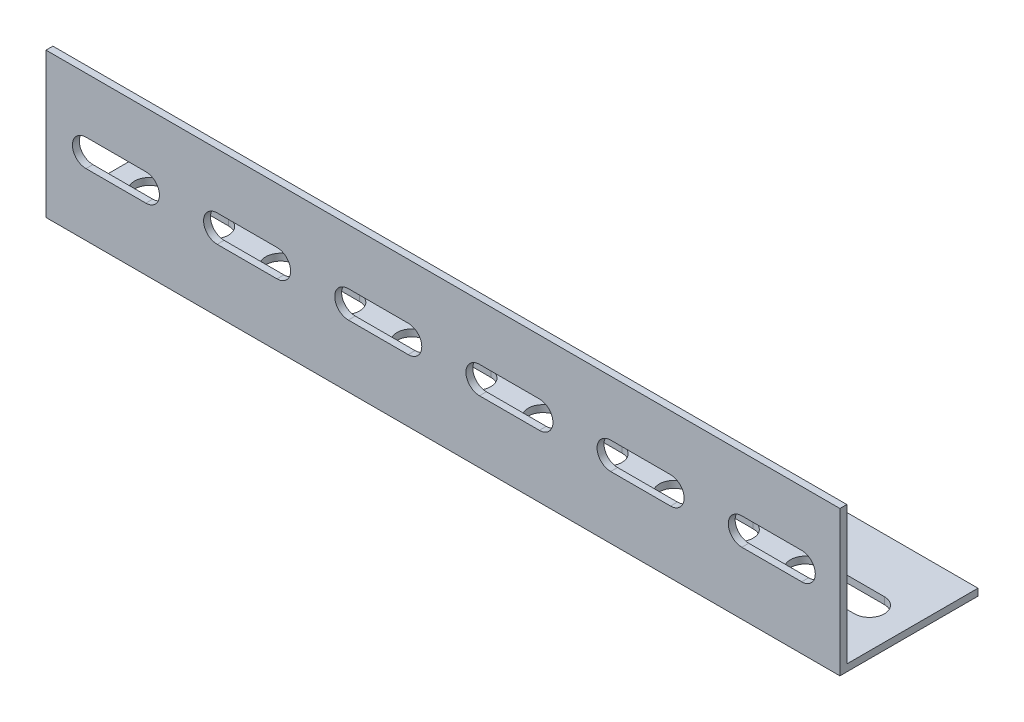
SolidWorks part; units mm, degrees
ref_plane "Front Plane" through (0, 0, 0) normal (0, 0, 1) x (1, 0, 0)
ref_plane "Top Plane" through (0, 0, 0) normal (0, 1, 0) x (1, 0, 0)
ref_plane "Right Plane" through (0, 0, 0) normal (1, 0, 0) x (0, 0, -1)
sketch "Sketch1" plane through (0, 0, 0) normal (0, 1, 0) x (1, 0, 0)
  line L1 (-75, 20) -> (75, 20)
  line L2 (-75, 20) -> (-75, -20)
  line L3 (-75, -20) -> (75, -20)
  line L4 (75, 20) -> (75, -20)
  line L5 (-75, 20) -> (75, -20) construction
  line L6 (-75, -20) -> (75, 20) construction
  point P0 (0, 0)
  dimension "D1" = 150
  dimension "D2" = 40
extrude "Boss-Extrude1" add sketch "Sketch1" along normal blind 2
sketch "Sketch2" plane through (0, 2, 0) normal (0, 1, 0) x (1, 0, 0)
  line L0 (75, -20) -> (75, 20) construction
  line L1 (-75, -20) -> (75, -20)
  line L2 (-75, -20) -> (-75, -18)
  line L3 (-75, -18) -> (75, -18)
  line L4 (75, -20) -> (75, -18)
  dimension "D1" = 2
extrude "Boss-Extrude2" add sketch "Sketch2" along normal blind 40
sketch "Sketch5" plane through (75, 0, 0) normal (1, 0, 0) x (0, 0, -1)
  line L12 (-20, 0) -> (20, 0)
  line L13 (20, 0) -> (20, 2)
  line L14 (20, 2) -> (-18, 2)
  line L15 (-18, 2) -> (-18, 42)
  line L16 (-18, 42) -> (-20, 42)
  line L17 (-20, 42) -> (-20, 0)
  line L18 (-20, 0) -> (20, 0)
  line L19 (20, 0) -> (20, 2)
  line L20 (20, 2) -> (-18, 2)
  line L21 (-18, 2) -> (-18, 42)
  line L22 (-18, 42) -> (-20, 42)
  line L23 (-20, 42) -> (-20, 0)
  dimension "D1" = 0
extrude "Boss-Extrude3" add sketch "Sketch5" along normal blind 80
sketch "Sketch6" plane through (0, 0, 18) normal (0, 0, -1) x (-1, 0, 0)
  line L0 (-105.9237, 25.9476) -> (-88.5878, 25.9476)
  line L1 (-143.9237, 25.9476) -> (-126.5878, 25.9476)
  line L3 (-143.9237, 18.0705) -> (-126.5878, 18.0705)
  line L5 (-143.9237, 25.9476) -> (-126.5878, 18.0705) construction
  line L6 (-143.9237, 18.0705) -> (-126.5878, 25.9476) construction
  line L7 (-105.9237, 18.0705) -> (-88.5878, 18.0705)
  line L8 (-67.9237, 25.9476) -> (-50.5878, 25.9476)
  line L9 (-67.9237, 18.0705) -> (-50.5878, 18.0705)
  line L10 (-29.9237, 25.9476) -> (-12.5878, 25.9476)
  line L11 (-29.9237, 18.0705) -> (-12.5878, 18.0705)
  line L12 (8.0763, 25.9476) -> (25.4122, 25.9476)
  line L13 (8.0763, 18.0705) -> (25.4122, 18.0705)
  line L14 (46.0763, 25.9476) -> (63.4122, 25.9476)
  line L15 (46.0763, 18.0705) -> (63.4122, 18.0705)
  arc A0 (-126.5878, 25.9476) -> (-126.5878, 18.0705) centre (-126.5878, 22.009) cw
  arc A1 (-143.9237, 25.9476) -> (-143.9237, 18.0705) centre (-143.9237, 22.009) ccw
  arc A2 (-88.5878, 25.9476) -> (-88.5878, 18.0705) centre (-88.5878, 22.009) cw
  arc A3 (-105.9237, 25.9476) -> (-105.9237, 18.0705) centre (-105.9237, 22.009) ccw
  arc A4 (-50.5878, 25.9476) -> (-50.5878, 18.0705) centre (-50.5878, 22.009) cw
  arc A5 (-67.9237, 25.9476) -> (-67.9237, 18.0705) centre (-67.9237, 22.009) ccw
  arc A6 (-12.5878, 25.9476) -> (-12.5878, 18.0705) centre (-12.5878, 22.009) cw
  arc A7 (-29.9237, 25.9476) -> (-29.9237, 18.0705) centre (-29.9237, 22.009) ccw
  arc A8 (25.4122, 25.9476) -> (25.4122, 18.0705) centre (25.4122, 22.009) cw
  arc A9 (8.0763, 25.9476) -> (8.0763, 18.0705) centre (8.0763, 22.009) ccw
  arc A10 (63.4122, 25.9476) -> (63.4122, 18.0705) centre (63.4122, 22.009) cw
  arc A11 (46.0763, 25.9476) -> (46.0763, 18.0705) centre (46.0763, 22.009) ccw
  point P0 (-135.2557, 22.009)
  dimension "D1" = 6
extrude "Cut-Extrude1" cut sketch "Sketch6" against normal blind 10
sketch "Sketch7" plane through (0, 0, 0) normal (0, -1, 0) x (1, 0, 0)
  line L0 (-27.0068, 4.3161) -> (-8.4465, 4.3161)
  line L1 (-65.0068, 4.3161) -> (-46.4465, 4.3161)
  line L3 (-65.0068, -4.3161) -> (-46.4465, -4.3161)
  line L5 (-65.0068, 4.3161) -> (-46.4465, -4.3161) construction
  line L6 (-65.0068, -4.3161) -> (-46.4465, 4.3161) construction
  line L7 (-27.0068, -4.3161) -> (-8.4465, -4.3161)
  line L8 (10.9932, 4.3161) -> (29.5535, 4.3161)
  line L9 (10.9932, -4.3161) -> (29.5535, -4.3161)
  line L10 (48.9932, 4.3161) -> (67.5535, 4.3161)
  line L11 (48.9932, -4.3161) -> (67.5535, -4.3161)
  line L12 (86.9932, 4.3161) -> (105.5535, 4.3161)
  line L13 (86.9932, -4.3161) -> (105.5535, -4.3161)
  line L14 (124.9932, 4.3161) -> (143.5535, 4.3161)
  line L15 (124.9932, -4.3161) -> (143.5535, -4.3161)
  arc A0 (-46.4465, 4.3161) -> (-46.4465, -4.3161) centre (-46.4465, 0) cw
  arc A1 (-65.0068, 4.3161) -> (-65.0068, -4.3161) centre (-65.0068, 0) ccw
  arc A2 (-8.4465, 4.3161) -> (-8.4465, -4.3161) centre (-8.4465, 0) cw
  arc A3 (-27.0068, 4.3161) -> (-27.0068, -4.3161) centre (-27.0068, 0) ccw
  arc A4 (29.5535, 4.3161) -> (29.5535, -4.3161) centre (29.5535, 0) cw
  arc A5 (10.9932, 4.3161) -> (10.9932, -4.3161) centre (10.9932, 0) ccw
  arc A6 (67.5535, 4.3161) -> (67.5535, -4.3161) centre (67.5535, 0) cw
  arc A7 (48.9932, 4.3161) -> (48.9932, -4.3161) centre (48.9932, 0) ccw
  arc A8 (105.5535, 4.3161) -> (105.5535, -4.3161) centre (105.5535, 0) cw
  arc A9 (86.9932, 4.3161) -> (86.9932, -4.3161) centre (86.9932, 0) ccw
  arc A10 (143.5535, 4.3161) -> (143.5535, -4.3161) centre (143.5535, 0) cw
  arc A11 (124.9932, 4.3161) -> (124.9932, -4.3161) centre (124.9932, 0) ccw
  point P0 (-55.7266, 0)
  dimension "D1" = 6
extrude "Cut-Extrude2" cut sketch "Sketch7" against normal blind 10
